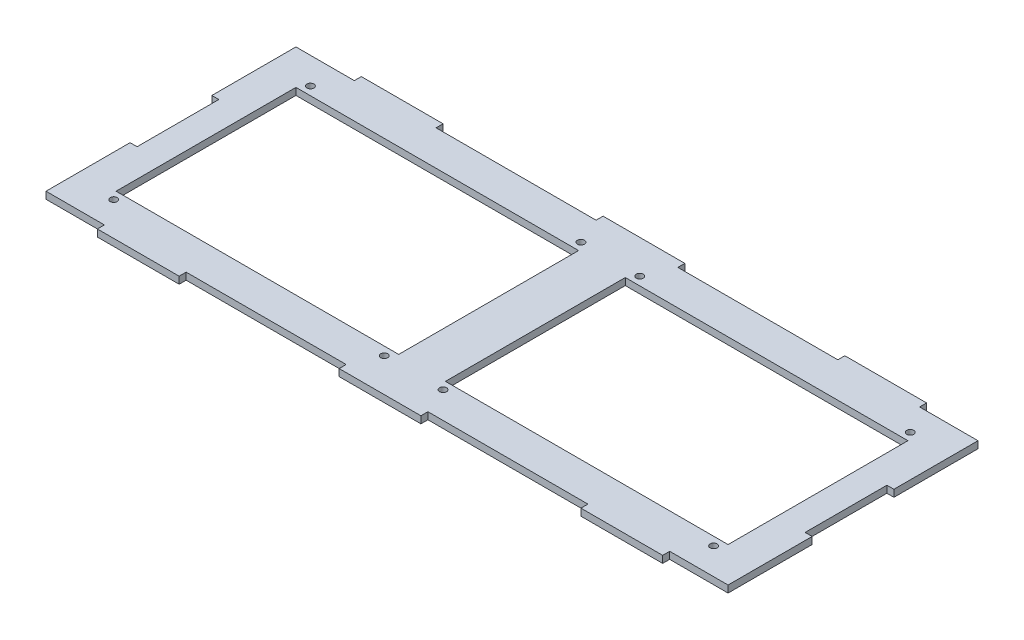
SolidWorks part; units mm, degrees
ref_plane "Front Plane" through (0, 0, 0) normal (0, 0, 1) x (1, 0, 0)
ref_plane "Top Plane" through (0, 0, 0) normal (0, 1, 0) x (1, 0, 0)
ref_plane "Right Plane" through (0, 0, 0) normal (1, 0, 0) x (0, 0, -1)
sketch "Sketch1" plane through (0, 0, 0) normal (0, 1, 0) x (1, 0, 0)
  line L1 (-146, 53.5) -> (146, 53.5)
  line L2 (-146, 53.5) -> (-146, -53.5)
  line L3 (-146, -53.5) -> (146, -53.5)
  line L4 (146, 53.5) -> (146, -53.5)
  line L5 (-146, 53.5) -> (146, -53.5) construction
  line L6 (-146, -53.5) -> (146, 53.5) construction
  point P0 (0, 0)
  point P6 (-210.2596, -52.4466)
  dimension "D1" = 292
  dimension "D2" = 107
extrude "Boss-Extrude1" add sketch "Sketch1" along normal blind 3
sketch "Sketch2" plane through (0, 3, 0) normal (0, 1, 0) x (1, 0, 0)
  line L0 (-146, 53.5) -> (-146, -53.5) construction
  line L1 (-131, 38.5) -> (-10, 38.5)
  line L2 (-131, 38.5) -> (-131, -38.5)
  line L3 (-131, -38.5) -> (-10, -38.5)
  line L4 (-10, 38.5) -> (-10, -38.5)
  line L5 (-131, 38.5) -> (-10, -38.5) construction
  line L6 (-131, -38.5) -> (-10, 38.5) construction
  line L7 (10, 38.5) -> (131, 38.5)
  line L8 (10, 38.5) -> (10, -38.5)
  line L9 (10, -38.5) -> (131, -38.5)
  line L10 (131, 38.5) -> (131, -38.5)
  line L11 (10, 38.5) -> (131, -38.5) construction
  line L12 (10, -38.5) -> (131, 38.5) construction
  line L13 (-146, -53.5) -> (146, -53.5) construction
  line L14 (146, -53.5) -> (146, 53.5) construction
  point P0 (-70.5, 0)
  point P5 (70.5, 0)
  dimension "D1" = 121
  dimension "D2" = 121
  dimension "D3" = 77
  dimension "D4" = 77
  dimension "D5" = 15
  dimension "D6" = 15
  dimension "D7" = 15
  dimension "D8" = 15
extrude "Cut-Extrude2" cut sketch "Sketch2" against normal blind 3 contours L2 L1 L4 L3
sketch "Sketch3" plane through (0, 3, 0) normal (0, 1, 0) x (1, 0, 0)
  line L1 (10, 38.5) -> (131, 38.5)
  line L2 (10, 38.5) -> (10, -38.5)
  line L3 (10, -38.5) -> (131, -38.5)
  line L4 (131, 38.5) -> (131, -38.5)
  line L5 (10, 38.5) -> (131, -38.5) construction
  line L6 (10, -38.5) -> (131, 38.5) construction
  line L7 (146, 53.5) -> (-146, 53.5) construction
  line L8 (-10, 38.5) -> (-10, -38.5) construction
  point P0 (70.5, 0)
  dimension "D1" = 121
  dimension "D2" = 77
  dimension "D3" = 15
  dimension "D4" = 20
extrude "Cut-Extrude3" cut sketch "Sketch3" against normal blind 3 contours L2 L1 L4 L3
sketch "Sketch4" plane through (0, 3, 0) normal (0, 1, 0) x (1, 0, 0)
  line L0 (-146, 53.5) -> (-146, -53.5) construction
  line L1 (-121, -53.5) -> (-86, -53.5)
  line L2 (-121, -53.5) -> (-121, -56.5)
  line L3 (-121, -56.5) -> (-86, -56.5)
  line L4 (-86, -53.5) -> (-86, -56.5)
  line L5 (-121, -53.5) -> (-86, -56.5) construction
  line L6 (-121, -56.5) -> (-86, -53.5) construction
  line L8 (-1.65, 0) -> (1.65, 0) construction
  line L9 (-86, 53.5) -> (-86, 56.5)
  line L10 (-121, 53.5) -> (-86, 53.5)
  line L11 (-121, 56.5) -> (-86, 56.5)
  line L12 (-121, 53.5) -> (-121, 56.5)
  line L13 (0, -1.65) -> (0, 1.65) construction
  line L14 (86, 53.5) -> (86, 56.5)
  line L15 (121, 53.5) -> (121, 56.5)
  line L16 (121, 56.5) -> (86, 56.5)
  line L17 (121, 53.5) -> (86, 53.5)
  line L18 (86, -53.5) -> (86, -56.5)
  line L19 (121, -53.5) -> (121, -56.5)
  line L20 (121, -53.5) -> (86, -53.5)
  line L21 (121, -56.5) -> (86, -56.5)
  line L22 (-146, -53.5) -> (146, -53.5) construction
  point P0 (-103.5, -55)
  dimension "D1" = 3
  dimension "D2" = 35
  dimension "D3" = 25
  dimension "D4" = 0
sketch "Sketch7" plane through (0, 3, 0) normal (0, 1, 0) x (1, 0, 0)
  line L1 (-17.5, -53.5) -> (17.5, -53.5)
  line L2 (-17.5, -53.5) -> (-17.5, -56.5)
  line L3 (-17.5, -56.5) -> (17.5, -56.5)
  line L4 (17.5, -53.5) -> (17.5, -56.5)
  line L5 (-17.5, -53.5) -> (17.5, -56.5) construction
  line L6 (-17.5, -56.5) -> (17.5, -53.5) construction
  line L7 (0, -1.65) -> (0, 1.65) construction
  line L8 (-1.65, 0) -> (1.65, 0) construction
  line L9 (-17.5, 56.5) -> (17.5, 56.5)
  line L10 (17.5, 53.5) -> (17.5, 56.5)
  line L11 (-17.5, 53.5) -> (17.5, 53.5)
  line L12 (-17.5, 53.5) -> (-17.5, 56.5)
  line L13 (-146, -53.5) -> (146, -53.5) construction
  point P0 (0, -55)
  dimension "D1" = 35
  dimension "D2" = 0
  dimension "D3" = 0
  dimension "D4" = 3
sketch "Sketch8" plane through (0, 3, 0) normal (0, 1, 0) x (1, 0, 0)
  line L0 (-1.65, 0) -> (1.65, 0) construction
  line L1 (146, 17.5) -> (143, 17.5)
  line L2 (146, 17.5) -> (146, -17.5)
  line L3 (146, -17.5) -> (143, -17.5)
  line L4 (143, 17.5) -> (143, -17.5)
  line L5 (146, 17.5) -> (143, -17.5) construction
  line L6 (146, -17.5) -> (143, 17.5) construction
  line L7 (146, -53.5) -> (146, 53.5) construction
  line L8 (0, -1.65) -> (0, 1.65) construction
  line L9 (-146, -17.5) -> (-143, -17.5)
  line L10 (-143, 17.5) -> (-143, -17.5)
  line L11 (-146, 17.5) -> (-143, 17.5)
  line L12 (-146, 17.5) -> (-146, -17.5)
  point P0 (144.5, 0)
  dimension "D1" = 35
  dimension "D2" = 3
  dimension "D3" = 0
  dimension "D4" = 0
extrude "Cut-Extrude7" cut sketch "Sketch8" against normal blind 3
extrude "Boss-Extrude2" add sketch "Sketch4" against normal blind 3
extrude "Boss-Extrude3" add sketch "Sketch7" against normal blind 3
sketch "Sketch9" plane through (0, 3, 0) normal (0, 1, 0) x (1, 0, 0)
  line L0 (-131, -38.5) -> (-10, -38.5) construction
  line L1 (-131, 38.5) -> (-131, -38.5) construction
  line L2 (-10, 38.5) -> (-10, -38.5) construction
  line L3 (-1.65, 0) -> (1.65, 0) construction
  line L4 (0, -1.65) -> (0, 1.65) construction
  circle A0 centre (-128.4, -42.1) radius 1.5
  circle A1 centre (-12.6, -42.1) radius 1.5
  circle A2 centre (-12.6, 42.1) radius 1.5
  circle A3 centre (-128.4, 42.1) radius 1.5
  circle A4 centre (12.6, -42.1) radius 1.5
  circle A5 centre (128.4, -42.1) radius 1.5
  circle A6 centre (128.4, 42.1) radius 1.5
  circle A7 centre (12.6, 42.1) radius 1.5
  dimension "D1" = 3
  dimension "D2" = 3.6
  dimension "D3" = 2.6
  dimension "D4" = 3
  dimension "D5" = 2.6
  dimension "D6" = 3.6
extrude "Cut-Extrude8" cut sketch "Sketch9" against normal blind 10
